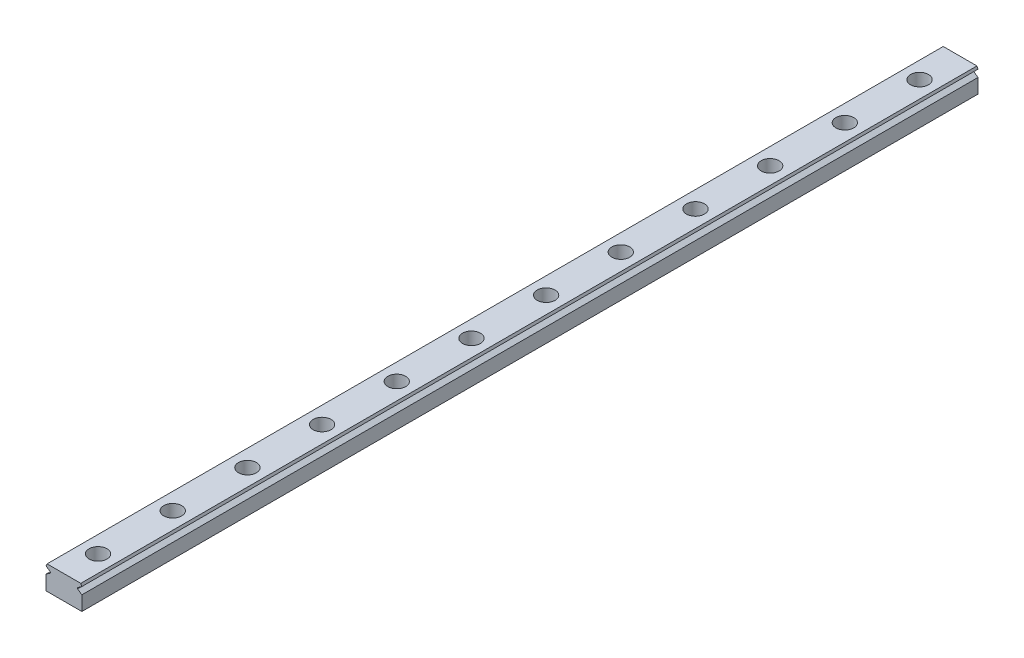
SolidWorks part; units mm, degrees
ref_plane "前视基准面" through (0, 0, 0) normal (0, 0, 1) x (1, 0, 0)
ref_plane "上视基准面" through (0, 0, 0) normal (0, 1, 0) x (1, 0, 0)
ref_plane "右视基准面" through (0, 0, 0) normal (1, 0, 0) x (0, 0, -1)
sketch "草图1" plane through (0, 0, 0) normal (0, 0, 1) x (1, 0, 0)
  line L0 (-76.7614, 75.3038) -> (-65.4736, 75.3038)
  line L1 (-65.4736, 75.3038) -> (-65.1175, 74.5402)
  line L2 (-65.1175, 74.5402) -> (-66.5493, 73.5377)
  line L3 (-66.5493, 73.5377) -> (-66.5493, 73.1469)
  line L4 (-66.5493, 73.1469) -> (-65.1175, 72.1443)
  line L5 (-65.1175, 72.1443) -> (-65.1175, 67.3038)
  line L6 (-65.1175, 67.3038) -> (-77.1175, 67.3038)
  line L7 (-77.1175, 67.3038) -> (-77.1175, 72.1443)
  line L8 (-77.1175, 72.1443) -> (-75.6857, 73.1469)
  line L9 (-75.6857, 73.1469) -> (-75.6857, 73.5377)
  line L10 (-75.6857, 73.5377) -> (-77.1175, 74.5402)
  line L11 (-77.1175, 74.5402) -> (-76.7614, 75.3038)
  dimension "D1" = 125
  dimension "D2" = 125
  dimension "D3" = 100
  dimension "D4" = 100
  dimension "D5" = 125
  dimension "D6" = 8
  dimension "D7" = 12
extrude "凸台-拉伸1" add sketch "草图1" along normal blind 300
sketch "草图2" plane through (0, 75.3038, 0) normal (0, 1, 0) x (1, 0, 0)
  line L0 (-65.4736, 0) -> (-76.7614, 0) construction
  line L1 (-71.1175, 0) -> (-71.1175, -300) construction
  line L2 (-65.4736, -300) -> (-76.7614, -300) construction
  circle A0 centre (-71.1175, -13.5781) radius 3
  circle A1 centre (-71.1175, -38.5781) radius 3
  circle A2 centre (-71.1175, -63.5781) radius 3
  circle A3 centre (-71.1175, -88.5781) radius 3
  circle A4 centre (-71.1175, -113.5781) radius 3
  circle A5 centre (-71.1175, -138.5781) radius 3
  circle A6 centre (-71.1175, -163.5781) radius 3
  circle A7 centre (-71.1175, -188.5781) radius 3
  circle A8 centre (-71.1175, -213.5781) radius 3
  circle A9 centre (-71.1175, -238.5781) radius 3
  circle A10 centre (-71.1175, -263.5781) radius 3
  circle A11 centre (-71.1175, -288.5781) radius 3
  point P0 (-71.1175, 0)
  dimension "D1" = 25
  dimension "D2" = 25
  dimension "D3" = 25
  dimension "D4" = 25
  dimension "D5" = 25
  dimension "D11" = 25
  dimension "D6" = 25
  dimension "D7" = 25
  dimension "D8" = 25
  dimension "D9" = 25
  dimension "D10" = 25
extrude "切除-拉伸1" cut sketch "草图2" against normal blind 4.5
sketch "草图5" plane through (0, 75.3038, 0) normal (0, 1, 0) x (1, 0, 0)
  circle A0 centre (-71.1175, -13.5781) radius 1.75
  circle A1 centre (-71.1175, -38.5781) radius 1.75
  circle A2 centre (-71.1175, -63.5781) radius 1.75
  circle A3 centre (-71.1175, -88.5781) radius 1.75
  circle A4 centre (-71.1175, -113.5781) radius 1.75
  circle A5 centre (-71.1175, -138.5781) radius 1.75
  circle A6 centre (-71.1175, -163.5781) radius 1.75
  circle A7 centre (-71.1175, -188.5781) radius 1.75
  circle A8 centre (-71.1175, -213.5781) radius 1.75
  circle A9 centre (-71.1175, -238.5781) radius 1.75
  circle A10 centre (-71.1175, -263.5781) radius 1.75
  circle A11 centre (-71.1175, -288.5781) radius 1.75
extrude "切除-拉伸2" cut sketch "草图5" against normal blind 8
